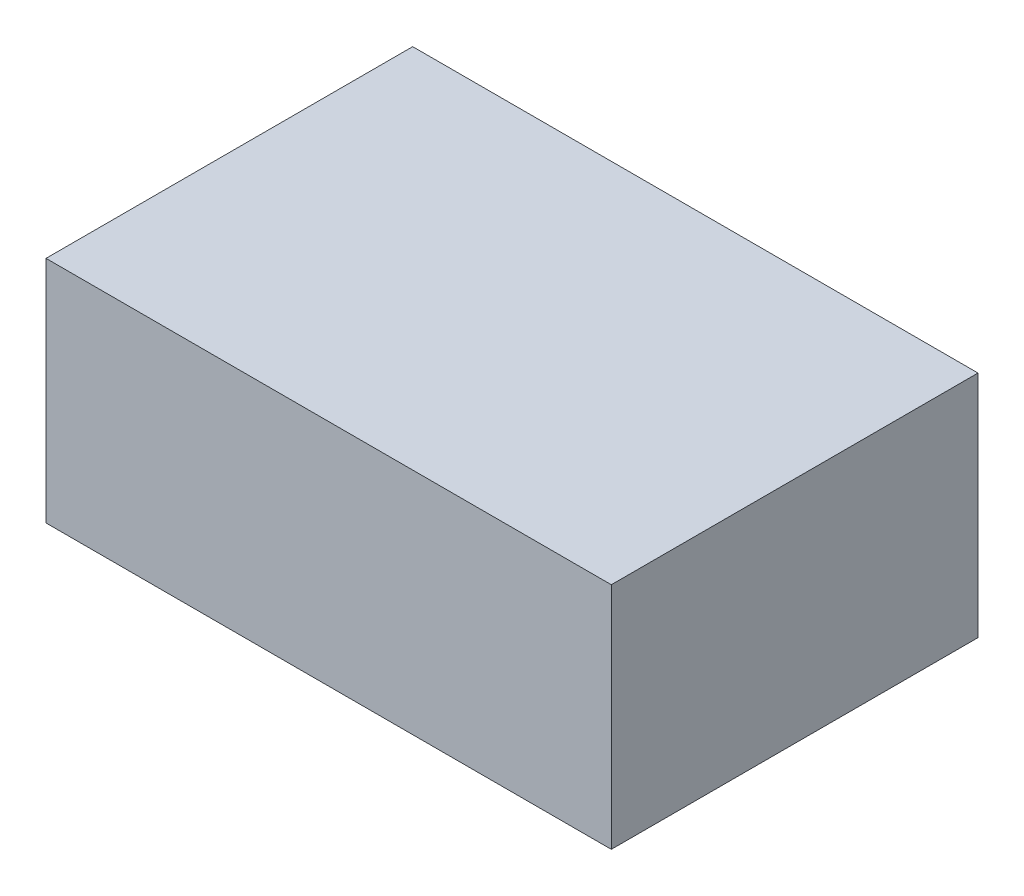
SolidWorks part; units mm, degrees
ref_plane "Front Plane" through (0, 0, 0) normal (0, 0, 1) x (1, 0, 0)
ref_plane "Top Plane" through (0, 0, 0) normal (0, 1, 0) x (1, 0, 0)
ref_plane "Right Plane" through (0, 0, 0) normal (1, 0, 0) x (0, 0, -1)
sketch "Sketch1" plane through (0, 0, 0) normal (0, 1, 0) x (1, 0, 0)
  line L1 (0, 0) -> (37, 0)
  line L2 (0, 0) -> (0, 24)
  line L3 (0, 24) -> (37, 24)
  line L4 (37, 0) -> (37, 24)
  dimension "D1" = 37
  dimension "D2" = 24
extrude "Boss-Extrude1" add sketch "Sketch1" along normal blind 15
